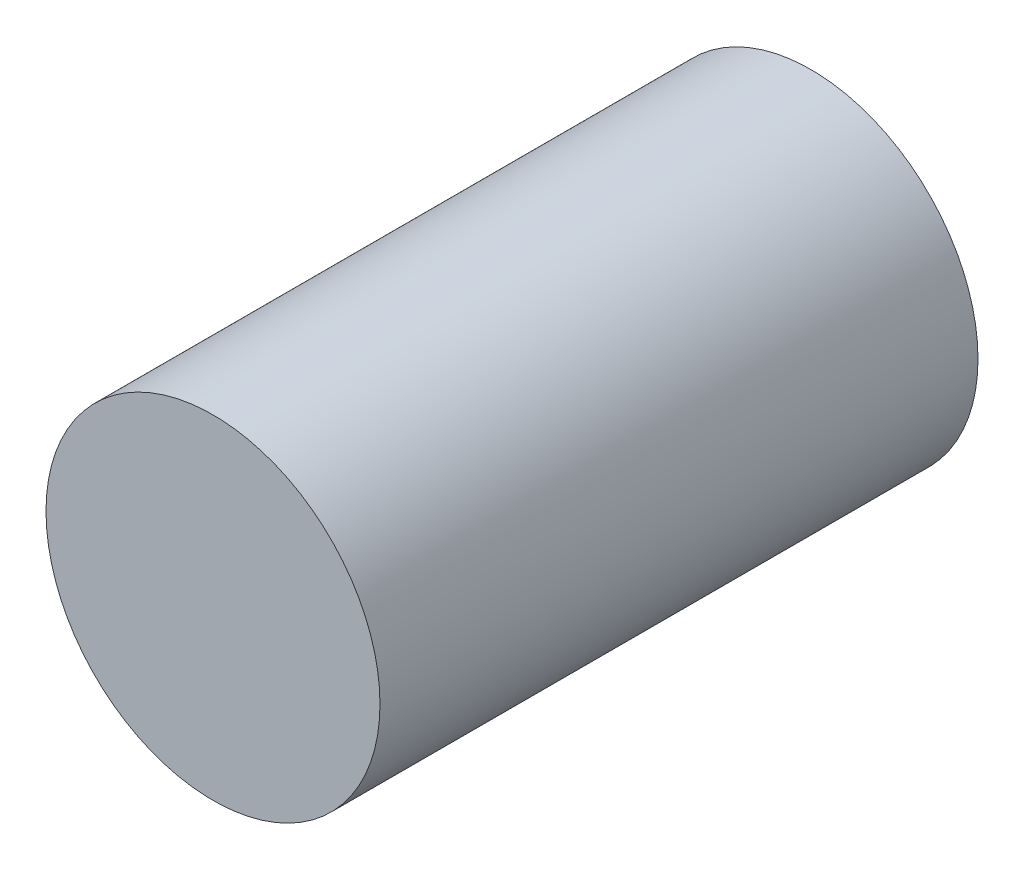
SolidWorks part; units mm, degrees
ref_plane "Front Plane" through (0, 0, 0) normal (0, 0, 1) x (1, 0, 0)
ref_plane "Top Plane" through (0, 0, 0) normal (0, 1, 0) x (1, 0, 0)
ref_plane "Right Plane" through (0, 0, 0) normal (1, 0, 0) x (0, 0, -1)
sketch "Sketch2" plane through (0, 0, 0) normal (0, 0, 1) x (1, 0, 0)
  circle A0 centre (0, 0) radius 32.004
  dimension "D1" = 64.008
extrude "Boss-Extrude1" add sketch "Sketch2" along normal blind 114.6048 contours A0
